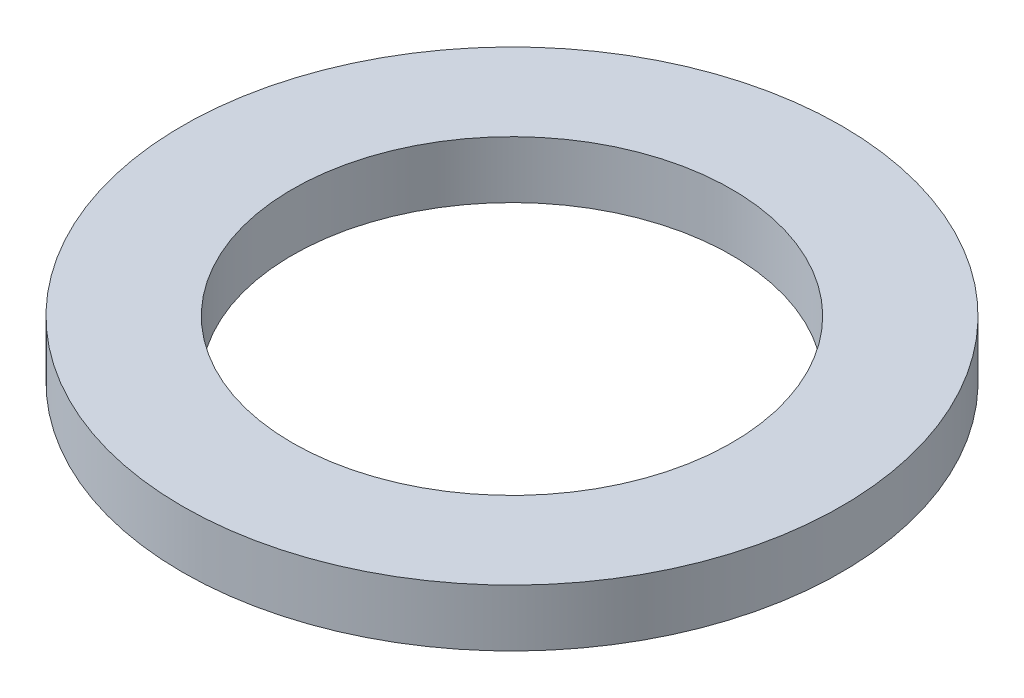
SolidWorks part; units mm, degrees
ref_plane "Front Plane" through (0, 0, 0) normal (0, 0, 1) x (1, 0, 0)
ref_plane "Top Plane" through (0, 0, 0) normal (0, 1, 0) x (1, 0, 0)
ref_plane "Right Plane" through (0, 0, 0) normal (1, 0, 0) x (0, 0, -1)
sketch "Sketch1" plane through (0, 0, 0) normal (0, 1, 0) x (1, 0, 0)
  circle A0 centre (0, 0) radius 9.525
  circle A1 centre (0, 0) radius 6.35
  dimension "D1" = 19.05
  dimension "D2" = 12.7
extrude "Boss-Extrude1" add sketch "Sketch1" along normal blind 1.65
